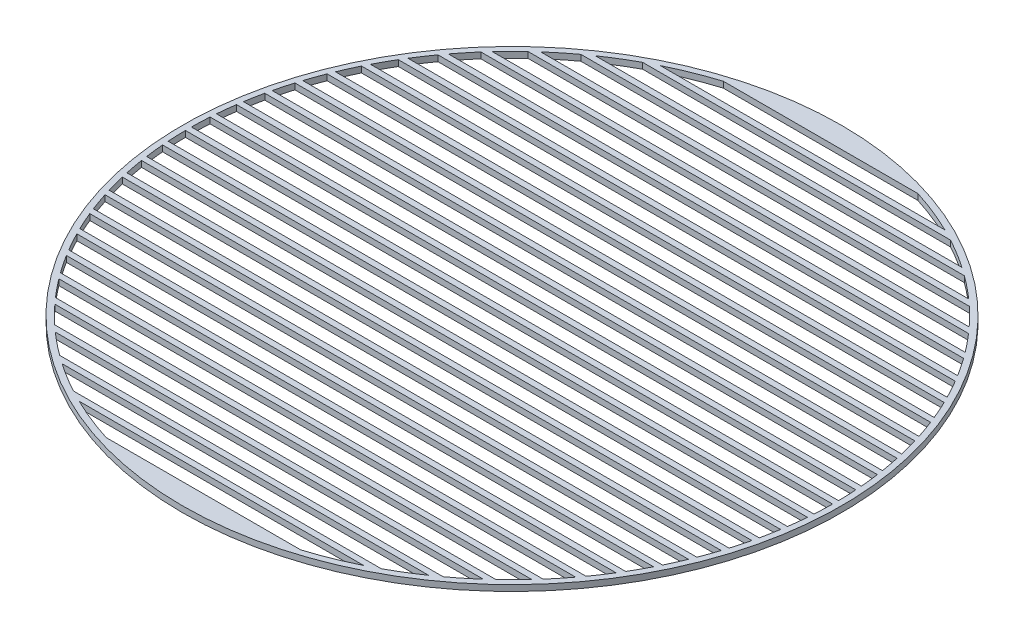
SolidWorks part; units mm, degrees
material "Plain Carbon Steel"
ref_plane "Front Plane" through (0, 0, 0) normal (0, 0, 1) x (1, 0, 0)
ref_plane "Top Plane" through (0, 0, 0) normal (0, 1, 0) x (1, 0, 0)
ref_plane "Right Plane" through (0, 0, 0) normal (1, 0, 0) x (0, 0, -1)
sketch "Sketch1" plane through (0, 0, 0) normal (0, 1, 0) x (1, 0, 0)
  line L0 (0, 0) -> (0, 270)
  line L1 (0, 0) -> (0, -270)
  line L2 (0, 0) -> (270, 0)
  line L3 (0, 0) -> (-270, 0)
  line L4 (0, 2.5) -> (-269.9884, 2.5)
  line L5 (0, -2.5) -> (-269.9884, -2.5)
  line L6 (0, 2.5) -> (269.9884, 2.5)
  line L7 (0, -2.5) -> (269.9884, -2.5)
  line L8 (-269.4323, -17.5) -> (269.4323, -17.5)
  line L9 (-269.0609, -22.5) -> (269.0609, -22.5)
  line L10 (-267.3832, -37.5) -> (267.3832, -37.5)
  line L11 (-266.6341, -42.5) -> (266.6341, -42.5)
  line L12 (-263.8063, -57.5) -> (263.8063, -57.5)
  line L13 (-262.6666, -62.5) -> (262.6666, -62.5)
  line L14 (-258.6383, -77.5) -> (258.6383, -77.5)
  line L15 (-257.087, -82.5) -> (257.087, -82.5)
  line L16 (-251.7812, -97.5) -> (251.7812, -97.5)
  line L17 (249.7874, -102.5) -> (-249.7874, -102.5)
  line L18 (243.0921, -117.5) -> (-243.0921, -117.5)
  line L19 (-240.6112, -122.5) -> (240.6112, -122.5)
  line L20 (232.3656, -137.5) -> (-232.3656, -137.5)
  line L21 (-229.3333, -142.5) -> (229.3333, -142.5)
  line L22 (-219.3029, -157.5) -> (219.3029, -157.5)
  line L23 (-215.6241, -162.5) -> (215.6241, -162.5)
  line L24 (-269.4323, 17.5) -> (269.4323, 17.5)
  line L25 (269.0609, 22.5) -> (-269.0609, 22.5)
  line L26 (-267.3832, 37.5) -> (267.3832, 37.5)
  line L27 (266.6341, 42.5) -> (-266.6341, 42.5)
  line L28 (-263.8063, 57.5) -> (263.8063, 57.5)
  line L29 (262.6666, 62.5) -> (-262.6666, 62.5)
  line L30 (-258.6383, 77.5) -> (258.6383, 77.5)
  line L31 (257.087, 82.5) -> (-257.087, 82.5)
  line L32 (-251.7812, 97.5) -> (251.7812, 97.5)
  line L33 (249.7874, 102.5) -> (-249.7874, 102.5)
  line L34 (-243.0921, 117.5) -> (243.0921, 117.5)
  line L35 (-240.6112, 122.5) -> (240.6112, 122.5)
  line L36 (232.3656, 137.5) -> (-232.3656, 137.5)
  line L37 (-229.3333, 142.5) -> (229.3333, 142.5)
  line L38 (219.3029, 157.5) -> (-219.3029, 157.5)
  line L39 (-215.6241, 162.5) -> (215.6241, 162.5)
  line L40 (-203.4545, 177.5) -> (203.4545, 177.5)
  line L41 (-198.9818, 182.5) -> (198.9818, 182.5)
  line L42 (-184.1026, 197.5) -> (184.1026, 197.5)
  line L43 (178.5882, 202.5) -> (-178.5882, 202.5)
  line L44 (-159.9805, 217.5) -> (159.9805, 217.5)
  line L45 (-152.9502, 222.5) -> (152.9502, 222.5)
  line L46 (-128.428, 237.5) -> (128.428, 237.5)
  line L47 (-203.4545, -177.5) -> (203.4545, -177.5)
  line L48 (198.9818, -182.5) -> (-198.9818, -182.5)
  line L49 (-184.1026, -197.5) -> (184.1026, -197.5)
  line L50 (178.5882, -202.5) -> (-178.5882, -202.5)
  line L51 (-159.9805, -217.5) -> (159.9805, -217.5)
  line L52 (152.9502, -222.5) -> (-152.9502, -222.5)
  line L53 (-128.428, -237.5) -> (128.428, -237.5)
  line L54 (-118.7171, 242.5) -> (118.7171, 242.5)
  line L55 (-81.2019, 257.5) -> (81.2019, 257.5)
  line L56 (-118.7171, -242.5) -> (118.7171, -242.5)
  line L57 (-81.2019, -257.5) -> (81.2019, -257.5)
  circle A0 centre (0, 0) radius 275
  circle A1 centre (0, 0) radius 270
  dimension "D1" = 550
  dimension "D2" = 540
  dimension "D3" = 2.5
  dimension "D4" = 2.5
  dimension "D5" = 15
  dimension "D6" = 5
  dimension "D7" = 15
  dimension "D8" = 5
  dimension "D9" = 15
  dimension "D10" = 5
  dimension "D11" = 15
  dimension "D12" = 5
  dimension "D13" = 15
  dimension "D14" = 5
  dimension "D15" = 15
  dimension "D16" = 5
  dimension "D17" = 15
  dimension "D18" = 5
  dimension "D19" = 15
  dimension "D20" = 5
  dimension "D21" = 15
  dimension "D22" = 5
  dimension "D23" = 15
  dimension "D24" = 5
  dimension "D25" = 15
  dimension "D26" = 5
  dimension "D27" = 15
  dimension "D28" = 5
  dimension "D29" = 15
  dimension "D30" = 5
  dimension "D31" = 15
  dimension "D32" = 5
  dimension "D33" = 15
  dimension "D34" = 5
  dimension "D35" = 15
  dimension "D36" = 5
  dimension "D37" = 15
  dimension "D38" = 5
  dimension "D39" = 15
  dimension "D40" = 5
  dimension "D41" = 15
  dimension "D42" = 5
  dimension "D43" = 15
  dimension "D44" = 15
  dimension "D45" = 5
  dimension "D46" = 15
  dimension "D47" = 5
  dimension "D48" = 15
  dimension "D49" = 5
  dimension "D50" = 15
  dimension "D51" = 5
  dimension "D52" = 15
  dimension "D53" = 5
  dimension "D54" = 15
extrude "Boss-Extrude1" add sketch "Sketch1" along normal blind 5 contours A0 A1 | L23 A1 L22 L1 | L22 A1 L23 L1 | L20 A1 L21 L1 | L21 A1 L20 L1 | L18 A1 L19 L1 | L19 A1 L18 L1 | L16 A1 L17 L1 | L17 A1 L16 L1 | L14 A1 L15 L1 | L15 A1 L14 L1 | L12 A1 L13 L1 | L13 A1 L12 L1 | L10 A1 L11 L1 | L11 A1 L10 L1 | L8 A1 L9 L1 | L9 A1 L8 L1 | L7 A1 L2 L1 | L2 A1 L6 L0 | L4 A1 L3 L0 | L3 A1 L5 L1 | L24 A1 L25 L0 | L25 A1 L24 L0 | L27 A1 L26 L0 | L29 A1 L28 L0 | L31 A1 L30 L0 | L33 A1 L32 L0 | L35 A1 L34 L0 | L37 A1 L36 L0 | L26 A1 L27 L0 | L28 A1 L29 L0 | L30 A1 L31 L0 | L32 A1 L33 L0 | L34 A1 L35 L0 | L36 A1 L37 L0 | L38 A1 L39 L0 | L39 A1 L38 L0 | L47 A1 L48 L1 | L48 A1 L47 L1 | L50 A1 L49 L1 | L49 A1 L50 L1 | L51 A1 L52 L1 | L52 A1 L51 L1 | L53 A1 L1 | L1 A1 L53 | L40 A1 L41 L0 | L41 A1 L40 L0 | L43 A1 L42 L0 | L42 A1 L43 L0 | L44 A1 L45 L0 | L45 A1 L44 L0 | L0 A1 L46 | L46 A1 L0 | L57 A1 L1 | L1 A1 L57 | L0 A1 L55 | L55 A1 L0
